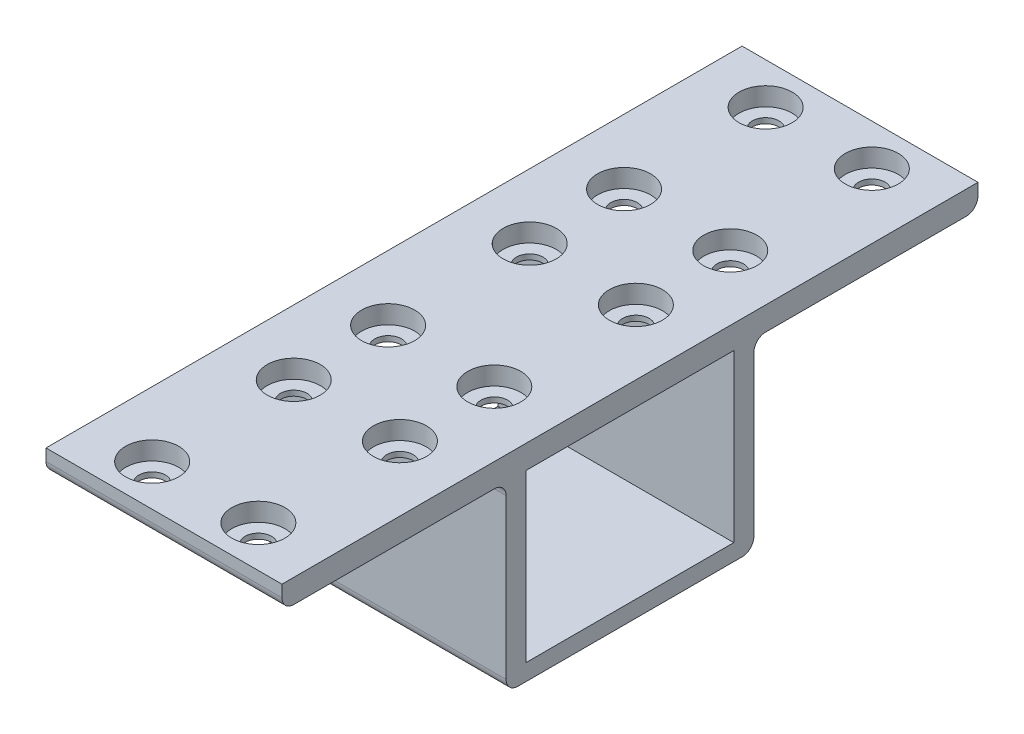
SolidWorks part; units mm, degrees
ref_plane "Front Plane" through (0, 0, 0) normal (0, 0, 1) x (1, 0, 0)
ref_plane "Top Plane" through (0, 0, 0) normal (0, 1, 0) x (1, 0, 0)
ref_plane "Right Plane" through (0, 0, 0) normal (1, 0, 0) x (0, 0, -1)
sketch "Sketch1" plane through (0, 0, 0) normal (1, 0, 0) x (0, 0, -1)
  line L5 (0, 0) -> (118, 0)
  line L6 (0, 0) -> (0, -4)
  line L8 (118, 0) -> (118, -4)
  line L13 (80, -4) -> (80, -35)
  line L14 (80, -35) -> (38, -35)
  line L15 (38, -35) -> (38, -4)
  line L17 (38, -4) -> (0, -4)
  line L18 (80, -4) -> (118, -4)
  line L19 (59, -35) -> (59, 0) construction
  line L20 (59, -4) -> (59, -32.2) construction
  line L25 (41.4, -4) -> (76.6, -4)
  line L26 (41.4, -4) -> (41.4, -32.2)
  line L27 (41.4, -32.2) -> (76.6, -32.2)
  line L28 (76.6, -4) -> (76.6, -32.2)
  line L29 (41.4, -18.1) -> (76.6, -18.1) construction
  dimension "D11" = 4
  dimension "D1" = 38
  dimension "D2" = 42
  dimension "D3" = 38
  dimension "D4" = 4
  dimension "D5" = 4
  dimension "D6" = 35.2
  dimension "D7" = 28.2
  dimension "D8" = 31
extrude "Boss-Extrude1" add sketch "Sketch1" against normal blind 40
fillet "Fillet1" radius 2 6 edges at (-20, -4, -80) (-20, -4, -38) (-20, -4, -118) (-20, -4, 0) (-20, -35, -80) (-20, -35, -38)
sketch "Sketch2" plane through (0, 0, 0) normal (0, 1, 0) x (1, 0, 0)
  line L0 (-20, 116) -> (-20, 82) construction
  line L5 (-35, 19) -> (-5, 19) construction
  line L6 (-5, 36) -> (-35, 2) construction
  line L7 (-5, 116) -> (-35, 116)
  line L8 (-5, 116) -> (-5, 82)
  line L9 (-5, 82) -> (-35, 82)
  line L10 (-35, 116) -> (-35, 82)
  line L11 (-5, 116) -> (-35, 82) construction
  line L12 (-5, 82) -> (-35, 116) construction
  line L13 (-5, 76.5) -> (-35, 76.5)
  line L14 (-5, 76.5) -> (-5, 41.5)
  line L15 (-5, 41.5) -> (-35, 41.5)
  line L16 (-35, 76.5) -> (-35, 41.5)
  line L17 (-5, 76.5) -> (-35, 41.5) construction
  line L18 (-5, 41.5) -> (-35, 76.5) construction
  line L19 (-5, 2) -> (-35, 36) construction
  line L20 (-40, 0) -> (0, 0) construction
  line L21 (-40, 118) -> (0, 118) construction
  line L22 (-40, 118) -> (-40, 0) construction
  line L23 (-20, 41.5) -> (-20, 76.5) construction
  line L24 (-35, 59) -> (-5, 59) construction
  line L25 (-35, 99) -> (-5, 99) construction
  line L26 (-20, 2) -> (-20, 36) construction
  line L27 (-35, 2) -> (-35, 36)
  line L28 (-5, 36) -> (-35, 36)
  line L29 (-5, 2) -> (-5, 36)
  line L30 (-5, 2) -> (-35, 2)
  point P5 (-20, 99)
  point P10 (-20, 59)
  point P18 (-40, 59)
  point P22 (-20, 0)
  point P25 (-20, 118)
  point P29 (-11, 87)
  point P33 (-11, 111)
  point P35 (-29, 111)
  point P36 (-29, 87)
  point P40 (-29, 31)
  point P41 (-29, 7)
  point P42 (-11, 7)
  point P43 (-11, 31)
  point P44 (-20, 19)
  point P45 (-11, 71)
  point P46 (-11, 47)
  point P49 (-29, 47)
  point P50 (-29, 71)
  dimension "D1" = 35
  dimension "D2" = 30
  dimension "D3" = 5.5
  dimension "D4" = 40
  dimension "D5" = 34
  dimension "D6" = 30
  dimension "D7" = 6
  dimension "D9" = 12
  dimension "D10" = 9
sketch "Sketch3" plane through (0, 0, 0) normal (1, 0, 0) x (0, 0, -1)
  line L0 (41.4, -4) -> (76.6, -32.2) construction
  line L1 (76.6, -4) -> (41.4, -32.2) construction
  point P8 (59, -18.1)
hole_wizard "CBORE for M4 Pan Head Machine Screw1" positions "3DSketch1" profile "Sketch4" counterbore size "M4" standard "ANSI Metric"
sketch3d "3DSketch1"
  point P0 (-11, 0, -111)
  point P3 (-29, 0, -111)
  point P6 (-11, 0, -87)
  point P9 (-29, 0, -87)
  point P12 (-11, 0, -71)
  point P15 (-11, 0, -47)
  point P18 (-29, 0, -47)
  point P21 (-29, 0, -71)
  point P24 (-11, 0, -31)
  point P27 (-29, 0, -31)
  point P30 (-29, 0, -7)
  point P33 (-11, 0, -7)
sketch "Sketch4" plane through (-11, 0, -111) normal (1, 0, 0) x (0, 0, 1)
  line L0 (0, 0) -> (0, 4)
  line L1 (0, 4) -> (2.25, 4)
  line L3 (2.25, 4) -> (2.25, 3.1)
  line L4 (2.25, 3.1) -> (4.5, 3.1)
  line L5 (4.5, 3.1) -> (4.5, 0)
  line L7 (4.5, 0) -> (0, 0)
  line L11 (0, -6.35) -> (0, 107.95) construction
  dimension "Thru Hole Dia." = 4.5
  dimension "Thru Hole Depth" = 4
  dimension "C'Bore Dia." = 9
  dimension "C'Bore Depth" = 3.1
ref_plane "Plane1" through (-39, 0, 0) normal (1, 0, 0) x (0, 0, -1)
sketch "Sketch5" plane through (-39, 0, 0) normal (1, 0, 0) x (0, 0, -1)
  line L1 (55, -35) -> (63, -35)
  line L2 (55, -35) -> (55, -39.7)
  line L4 (63, -35) -> (63, -39.7)
  line L5 (40, -35) -> (78, -35) construction
  line L6 (63, -39.7) -> (55, -39.7)
  circle A1 centre (59, -38) radius 1.35
  point P4 (59, -35)
  point P5 (59, -35)
  dimension "D3" = 2.7
  dimension "D2" = 3
  dimension "D1" = 8
  dimension "D4" = 4.7
extrude "Boss-Extrude2" add sketch "Sketch5" along normal blind 3
ref_plane "Plane2" through (-28, 0, 0) normal (1, 0, 0) x (0, 0, -1)
sketch "Sketch6" plane through (-28, 0, 0) normal (1, 0, 0) x (0, 0, -1)
  line L3 (55, -35) -> (55, -39.7)
  line L4 (63, -39.7) -> (63, -35)
  line L5 (63, -35) -> (55, -35)
  line L6 (55, -35) -> (55, -39.7)
  line L7 (63, -39.7) -> (63, -35)
  line L8 (63, -35) -> (55, -35)
  line L10 (55, -39.7) -> (63, -39.7)
  line L11 (55, -39.7) -> (63, -39.7)
  circle A0 centre (59, -38) radius 1.35 construction
  circle A3 centre (59, -38) radius 1.35
  dimension "D1" = 0
extrude "Boss-Extrude3" add sketch "Sketch6" along normal blind 6
sketch "Sketch7" plane through (-28, 0, 0) normal (-1, 0, 0) x (0, 0, 1)
  line L1 (-63, -37) -> (-62.2, -37)
  line L2 (-63, -37) -> (-63, -39.4)
  line L3 (-63, -39.4) -> (-62.2, -39.4)
  line L4 (-62.2, -37) -> (-62.2, -39.4)
  line L6 (-55, -39.4) -> (-55.8, -39.4)
  line L7 (-55, -37) -> (-55.8, -37)
  line L8 (-55.8, -37) -> (-55.8, -39.4)
  line L9 (-55, -37) -> (-55, -39.4)
  line L10 (-55, -35) -> (-55, -39.7) construction
  line L11 (-63, -35) -> (-55, -35) construction
  line L12 (-63, -39.7) -> (-63, -35) construction
  dimension "D1" = 0.8
  dimension "D2" = 0.8
  dimension "D3" = 2.4
  dimension "D4" = 2.4
  dimension "D5" = 2
  dimension "D6" = 2
  dimension "D7" = 0.8
extrude "Boss-Extrude4" add sketch "Sketch7" along normal up to next
sketch "Sketch8" plane through (-36, 0, 0) normal (1, 0, 0) x (0, 0, -1)
  line L0 (63, -39.7) -> (63, -39.4) construction
  line L1 (63, -37) -> (62.2, -37)
  line L2 (63, -37) -> (63, -39.4)
  line L3 (63, -39.4) -> (62.2, -39.4)
  line L4 (62.2, -37) -> (62.2, -39.4)
  line L5 (63, -35) -> (55, -35) construction
  line L6 (55, -35) -> (55, -37) construction
  line L7 (55, -37) -> (55.8, -37)
  line L8 (55, -37) -> (55, -39.4)
  line L9 (55, -39.4) -> (55.8, -39.4)
  line L10 (55.8, -37) -> (55.8, -39.4)
  dimension "D1" = 0.8
  dimension "D2" = 2
  dimension "D3" = 2.4
  dimension "D4" = 0.8
  dimension "D5" = 2
  dimension "D6" = 2.4
extrude "Boss-Extrude5" add sketch "Sketch8" along normal blind 2
